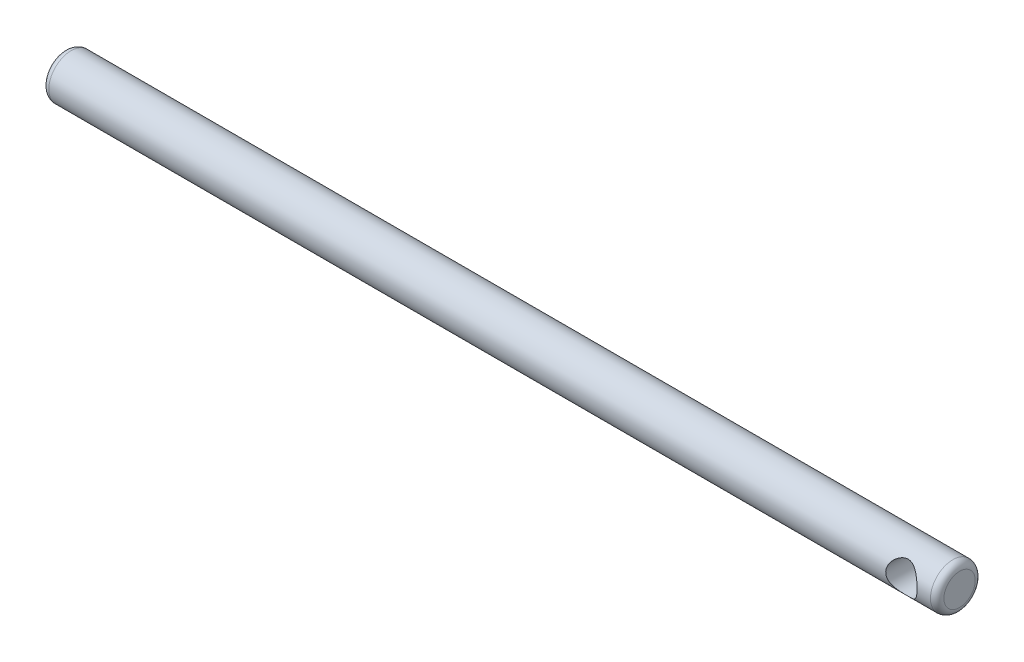
SolidWorks part; units mm, degrees
ref_plane "Ebene vorne" through (0, 0, 0) normal (0, 0, 1) x (1, 0, 0)
ref_plane "Ebene oben" through (0, 0, 0) normal (0, 1, 0) x (1, 0, 0)
ref_plane "Ebene rechts" through (0, 0, 0) normal (1, 0, 0) x (0, 0, -1)
sketch "Skizze1" plane through (0, 0, 0) normal (0, 0, 1) x (1, 0, 0)
  line L1 (0, 0) -> (-100, 0)
  line L2 (0, 0) -> (0, 2.5)
  line L3 (0, 2.5) -> (-100, 2.5)
  line L4 (-100, 0) -> (-100, 2.5)
  dimension "D1" = 2.5
  dimension "D2" = 100
revolve "Rotation1" add sketch "Skizze1" angle 360 about L1
fillet "Verrundung1" radius 0.75 1 edges at (-100, 2.5, 0)
fillet "Verrundung2" radius 0.75 1 edges at (0, 2.5, 0)
hole_wizard "Ø3.5 (3.5) Durchmesser Bohrung1" positions "3D-Skizze2" profile "Skizze3" hole size "Ø3.5" standard "DIN" end condition through all
sketch3d "3D-Skizze2"
  point P0 (-4, 0.063, 2.4992)
  dimension "D1" = 4
sketch "Skizze3" plane through (-4, 0.063, 2.4992) normal (1, 0, 0) x (0, -0.9997, 0.0252)
  line L0 (0, 0) -> (0, 5.0622)
  line L1 (0, 5.0622) -> (1.75, 5.0622)
  line L2 (1.75, 5.0622) -> (1.75, 0)
  line L5 (1.75, 0) -> (0, 0)
  line L11 (0, -6.35) -> (0, 107.95) construction
  dimension "Bohrerdurchmesser" = 3.5
  dimension "Bohrungstiefe" = 5.0622
